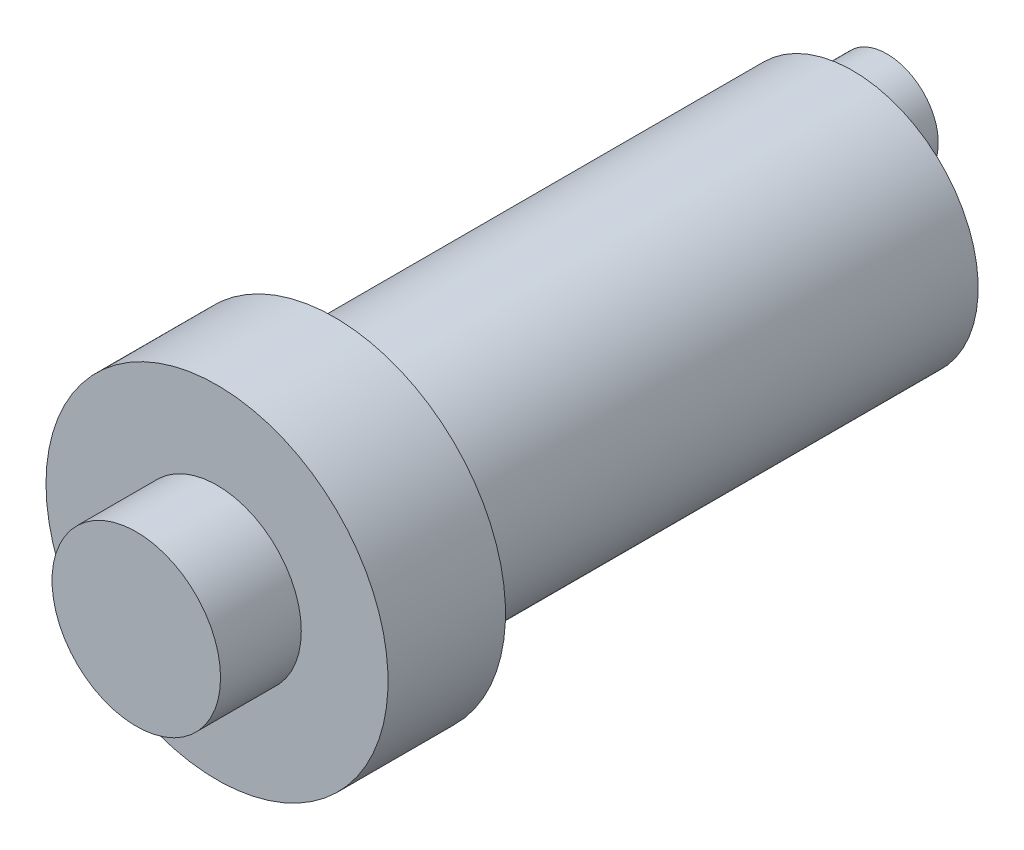
SolidWorks part; units mm, degrees
ref_plane "Plan de face" through (0, 0, 0) normal (0, 0, 1) x (1, 0, 0)
ref_plane "Plan de dessus" through (0, 0, 0) normal (0, 1, 0) x (1, 0, 0)
ref_plane "Plan de droite" through (0, 0, 0) normal (1, 0, 0) x (0, 0, -1)
sketch "Esquisse1" plane through (0, 0, 0) normal (0, 0, 1) x (1, 0, 0)
  circle A0 centre (0, 0) radius 5.74
  dimension "D1" = 11.48
extrude "Boss.-Extru.1" add sketch "Esquisse1" along normal blind 5.5
sketch "Esquisse2" plane through (0, 0, 0) normal (0, 0, -1) x (-1, 0, 0)
  circle A0 centre (0, 0) radius 11.65
  dimension "D1" = 23.3
extrude "Boss.-Extru.2" add sketch "Esquisse2" along normal blind 8
sketch "Esquisse3" plane through (0, 0, -8) normal (0, 0, -1) x (-1, 0, 0)
  circle A0 centre (0, 0) radius 8.55
  dimension "D1" = 17.1
extrude "Boss.-Extru.3" add sketch "Esquisse3" along normal blind 35.3
sketch "Esquisse4" plane through (0, 0, -43.3) normal (0, 0, -1) x (-1, 0, 0)
  circle A0 centre (4.8653, 0) radius 3.5
  point P2 (4.8653, 0)
  dimension "D1" = 7
extrude "Boss.-Extru.4" add sketch "Esquisse4" along normal blind 7.2
